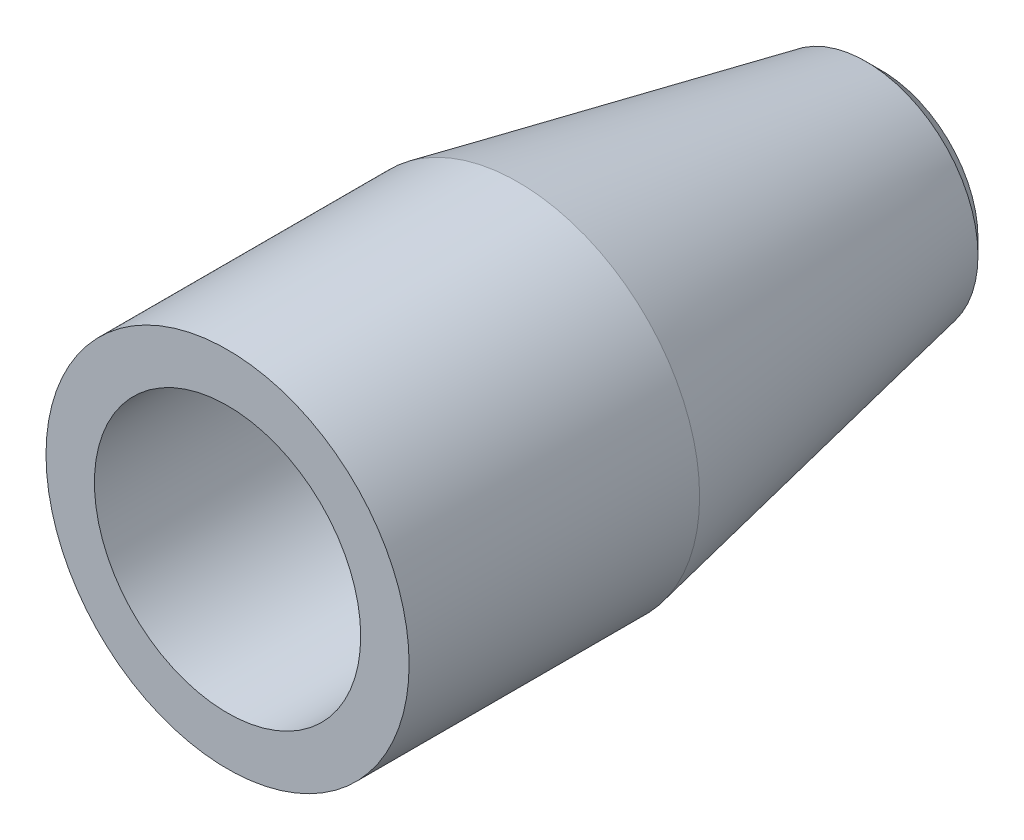
SolidWorks part; units mm, degrees
ref_plane "Front Plane" through (0, 0, 0) normal (0, 0, 1) x (1, 0, 0)
ref_plane "Top Plane" through (0, 0, 0) normal (0, 1, 0) x (1, 0, 0)
ref_plane "Right Plane" through (0, 0, 0) normal (1, 0, 0) x (0, 0, -1)
sketch "Sketch1" plane through (0, 0, 0) normal (0, 1, 0) x (1, 0, 0)
  line L0 (0, 0) -> (0, 10.0991) construction
  line L1 (2, 9.2376) -> (2, 7.2376)
  line L2 (2, 7.2376) -> (2.9, 7.2376)
  line L3 (2.9, 7.2376) -> (5.5, -5.7624)
  line L4 (5.5, -5.7624) -> (5.5, -17.7624)
  line L5 (5.5, -17.7624) -> (7.5, -17.7624)
  line L6 (7.5, -17.7624) -> (7.5, -5.7624)
  line L7 (7.5, -5.7624) -> (4.5, 9.2376)
  line L8 (4.5, 9.2376) -> (2, 9.2376)
  point P7 (0, 0)
  point P12 (9.5055, -6.7624)
  dimension "D1" = 27
  dimension "D2" = 9
  dimension "D3" = 12
  dimension "D4" = 2
  dimension "D5" = 2
  dimension "D6" = 4
  dimension "D7" = 15
  dimension "D8" = 15
revolve "Revolve1" add sketch "Sketch1" angle 360 about L0
chamfer "Chamfer1" distance 0.5 angle 45 1 edges at (4.5, 0, -9.2376)
